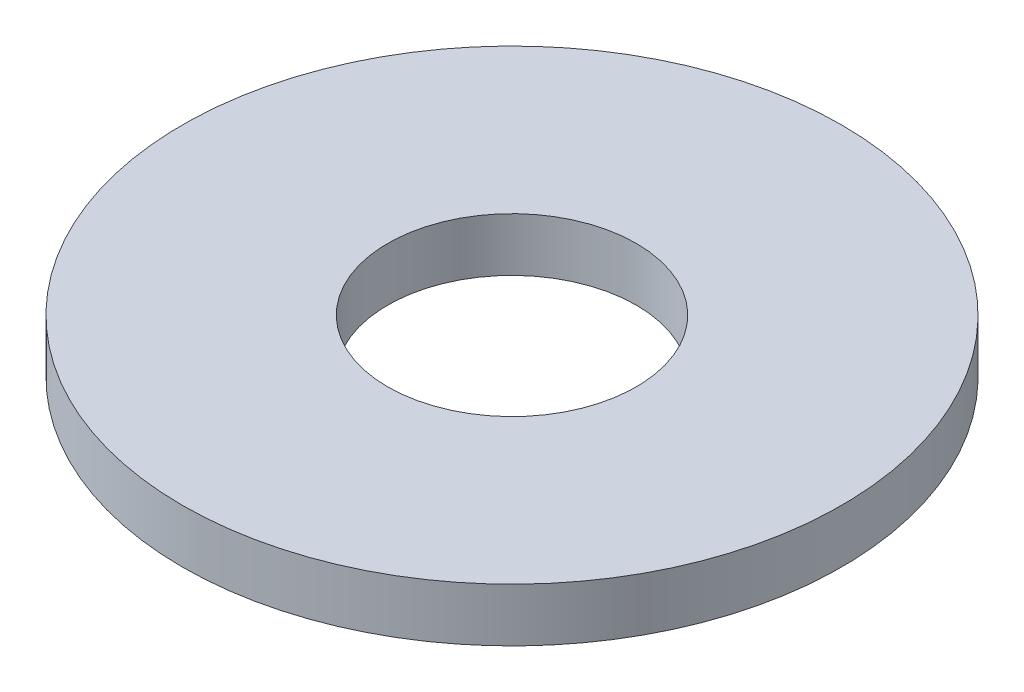
SolidWorks part; units mm, degrees
material "Plain Carbon Steel"
ref_plane "Front Plane" through (0, 0, 0) normal (0, 0, 1) x (1, 0, 0)
ref_plane "Top Plane" through (0, 0, 0) normal (0, 1, 0) x (1, 0, 0)
ref_plane "Right Plane" through (0, 0, 0) normal (1, 0, 0) x (0, 0, -1)
sketch "Sketch1" plane through (0, 0, 0) normal (0, 1, 0) x (1, 0, 0)
  circle A0 centre (0, 0) radius 11.1125
  circle A1 centre (0, 0) radius 4.191
  dimension "D1" = 8.382
  dimension "D2" = 22.225
extrude "Boss-Extrude1" add sketch "Sketch1" along normal blind 1.8034
